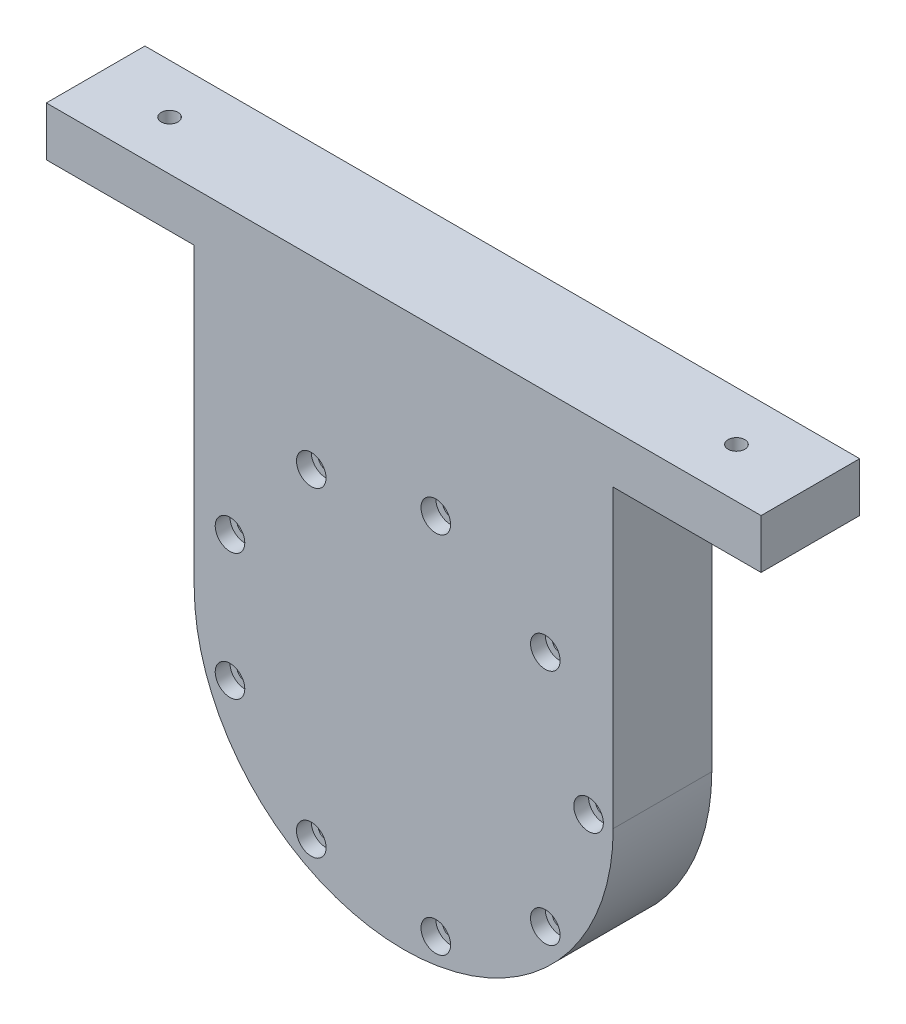
SolidWorks part; units mm, degrees
ref_plane "Front Plane" through (0, 0, 0) normal (0, 0, 1) x (1, 0, 0)
ref_plane "Top Plane" through (0, 0, 0) normal (0, 1, 0) x (1, 0, 0)
ref_plane "Right Plane" through (0, 0, 0) normal (1, 0, 0) x (0, 0, -1)
sketch "Sketch1" plane through (0, 0, 0) normal (0, 0, 1) x (1, 0, 0)
  line L0 (0, 0) -> (37.5, 0) construction
  line L1 (-42.5, 0) -> (-42.5, 60)
  line L2 (42.5, 0) -> (42.5, 60)
  line L3 (-42.5, 60) -> (-72.5, 60)
  line L4 (42.5, 60) -> (72.5, 60)
  line L5 (-72.5, 60) -> (-72.5, 70)
  line L6 (-72.5, 70) -> (72.5, 70)
  line L7 (72.5, 70) -> (72.5, 60)
  arc A0 (-42.5, 0) -> (42.5, 0) centre (0, 0) ccw
  circle A1 centre (37.5, 0) radius 1.6
  circle A2 centre (28.7267, -24.1045) radius 1.6
  circle A3 centre (6.5118, -36.9303) radius 1.6
  circle A4 centre (-18.75, -32.476) radius 1.6
  circle A5 centre (-35.2385, -12.8258) radius 1.6
  circle A6 centre (-35.2385, 12.8258) radius 1.6
  circle A7 centre (-18.75, 32.476) radius 1.6
  circle A8 centre (6.5118, 36.9303) radius 1.6
  circle A9 centre (28.7267, 24.1045) radius 1.6
  point P23 (0, 0)
  dimension "D1" = 85
  dimension "D3" = 3.2
  dimension "D4" = 9
  dimension "D2" = 37.5
  dimension "D5" = 60
  dimension "D6" = 60
  dimension "D7" = 30
  dimension "D8" = 30
  dimension "D9" = 10
extrude "Boss-Extrude2" add sketch "Sketch1" along normal blind 20
sketch "Sketch2" plane through (0, 0, 20) normal (0, 0, 1) x (1, 0, 0)
  circle A0 centre (6.5118, 36.9303) radius 3
  circle A1 centre (28.7267, 24.1045) radius 3
  circle A2 centre (37.5, 0) radius 3
  circle A3 centre (28.7267, -24.1045) radius 3
  circle A4 centre (6.5118, -36.9303) radius 3
  circle A5 centre (-18.75, -32.476) radius 3
  circle A6 centre (-35.2385, -12.8258) radius 3
  circle A7 centre (-35.2385, 12.8258) radius 3
  circle A8 centre (-18.75, 32.476) radius 3
  point P4 (30.2733, 28.1578)
  point P5 (0, 0)
  point P21 (0, 0)
  dimension "D1" = 6
  dimension "D2" = 9
extrude "Cut-Extrude1" cut sketch "Sketch2" against normal blind 3
sketch "Sketch3" plane through (0, 60, 0) normal (0, -1, 0) x (1, 0, 0)
  line L0 (-72.5, 10) -> (72.5, 10) construction
  line L1 (-72.5, 20) -> (-72.5, 0) construction
  line L2 (72.5, 20) -> (72.5, 0) construction
  circle A0 centre (57.5, 10) radius 1.7
  circle A1 centre (-57.5, 10) radius 1.7
  dimension "D1" = 3.4
  dimension "D2" = 3.4
  dimension "D3" = 15
  dimension "D4" = 15
extrude "Cut-Extrude2" cut sketch "Sketch3" against normal through all
